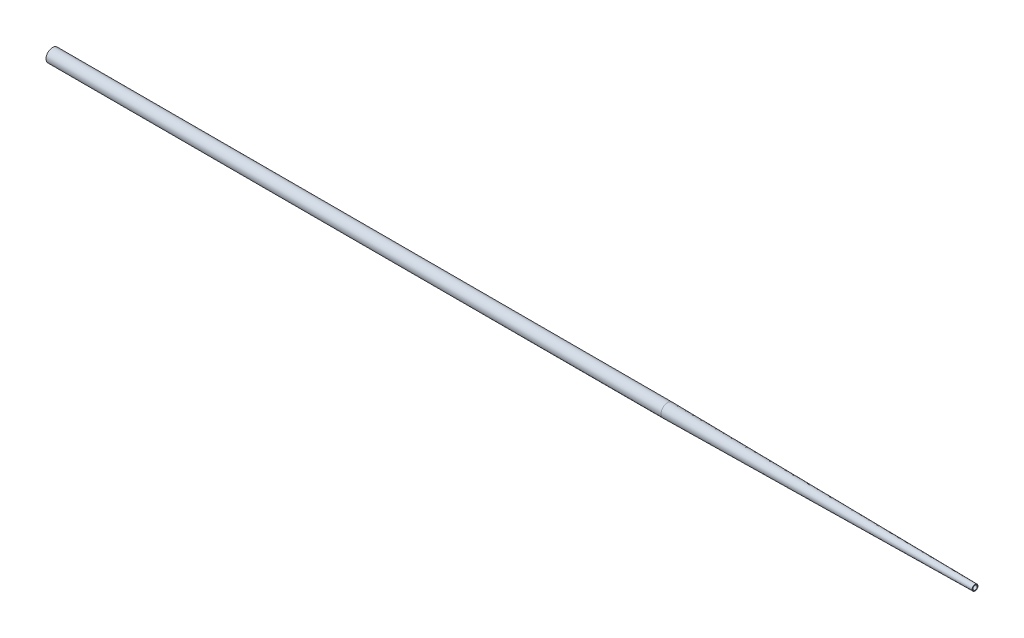
SolidWorks part; units mm, degrees
material "Hexcel AS4C (3000 Filaments)"
ref_plane "Front Plane" through (0, 0, 0) normal (0, 0, 1) x (1, 0, 0)
ref_plane "Top Plane" through (0, 0, 0) normal (0, 1, 0) x (1, 0, 0)
ref_plane "Right Plane" through (0, 0, 0) normal (1, 0, 0) x (0, 0, -1)
sketch "Sketch1" plane through (0, 0, 0) normal (0, 1, 0) x (1, 0, 0)
  line L0 (-229.2075, 14.0142) -> (-43.6666, 14.0142) construction
  line L1 (-225.3505, 22.5142) -> (-225.3505, 21.5142)
  line L2 (-225.3505, 21.5142) -> (574.6495, 21.5142)
  line L4 (574.6495, 22.5142) -> (-225.3505, 22.5142)
  line L5 (574.6495, 21.5142) -> (974.6495, 16.7922)
  line L6 (574.6495, 22.5142) -> (974.6495, 17.7922)
  line L7 (974.6495, 17.7922) -> (974.6495, 16.7922)
  dimension "D1" = 0
  dimension "D3" = 8.5
  dimension "D4" = 1
  dimension "D5" = 800
  dimension "D6" = 400
revolve "Revolve1" add sketch "Sketch1" angle 360 about L0
